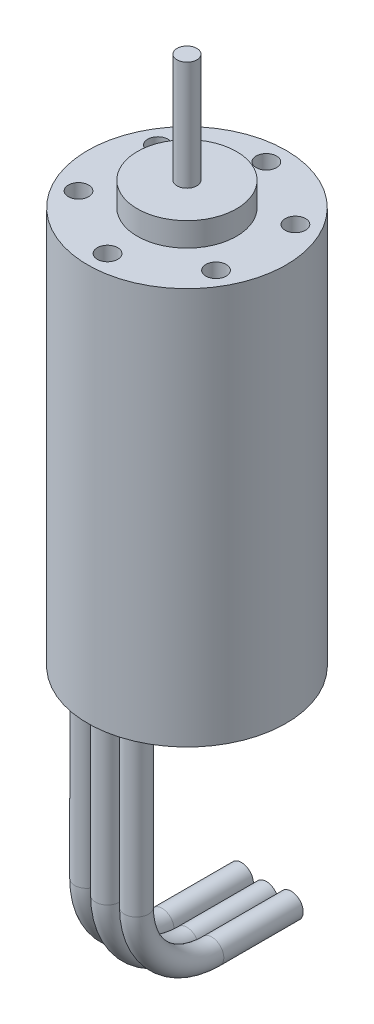
SolidWorks part; units mm, degrees
ref_plane "Front Plane" through (0, 0, 0) normal (0, 0, 1) x (1, 0, 0)
ref_plane "Top Plane" through (0, 0, 0) normal (0, 1, 0) x (1, 0, 0)
ref_plane "Right Plane" through (0, 0, 0) normal (1, 0, 0) x (0, 0, -1)
sketch "Sketch1" plane through (0, 0, 0) normal (0, 0, 1) x (1, 0, 0)
  line L0 (0, 0) -> (0, 55.8) construction
  line L1 (0, 55.8) -> (1, 55.8)
  line L2 (1, 55.8) -> (1, 44.8)
  line L3 (1, 44.8) -> (5, 44.8)
  line L4 (10, 42.4) -> (10, 2.4)
  line L5 (0, 0) -> (5, 0)
  line L6 (0, 0) -> (0, 55.8)
  line L7 (5, 0) -> (5, 2.4)
  line L8 (5, 2.4) -> (10, 2.4)
  line L9 (5, 44.8) -> (5, 42.4)
  line L10 (5, 42.4) -> (10, 42.4)
  dimension "D1" = 2.4
  dimension "D2" = 20
  dimension "D3" = 2
  dimension "D4" = 40
  dimension "D5" = 2.4
  dimension "D6" = 11
  dimension "D7" = 5
  dimension "D8" = 5
revolve "Revolve1" add sketch "Sketch1" angle 360 about L0
hole_wizard "M2.5x0.45 Tapped Hole1" positions "Sketch3" profile "Sketch2" tap size "M2.5x0.45" standard "ANSI Metric"
sketch "Sketch3" plane through (0, 42.4, 0) normal (0, 1, 0) x (1, 0, 0)
  line L1 (0, 0) -> (0, 8) construction
  point P0 (0, 8)
  dimension "D1" = 8
sketch "Sketch2" plane through (0, 42.4, -8) normal (1, 0, 0) x (0, 0, 1)
  line L0 (0, 0) -> (0, 4.6159)
  line L1 (0, 4.6159) -> (1.025, 4)
  line L2 (1.025, 4) -> (1.025, 0)
  line L5 (1.025, 0) -> (0, 0)
  line L10 (0, 4.6159) -> (-1.025, 4) construction
  line L11 (0, -6.35) -> (0, 107.95) construction
  dimension "Tap Drill Dia." = 2.05
  dimension "Tap Drill Depth" = 4
  dimension "Drill Angle" = 118
cosmetic thread "Hole Thread1" parameters "D1"=4, "D2"=2.5
pattern_circular "CirPattern1" count 6 over 360 about axis through (0, 0, 0) along (0, 1, 0) of "M2.5x0.45 Tapped Hole1"
sketch "Sketch4" plane through (0, 2.4, 0) normal (0, -1, 0) x (-1, 0, 0)
  line L0 (2.5078, -7.5968) -> (0, -8) construction
  line L1 (0, -8) -> (-2.5078, -7.5968) construction
  line L2 (-2.5078, -7.5968) -> (0, 0) construction
  line L3 (0, 0) -> (0, -8) construction
  line L4 (2.5078, -7.5968) -> (0, 0) construction
  circle A0 centre (-2.5078, -7.5968) radius 1.2065
  circle A1 centre (0, -8) radius 1.2065
  circle A2 centre (2.5078, -7.5968) radius 1.2065
  point P0 (-2.5078, -7.5968)
  point P1 (0, -8)
  point P2 (2.5078, -7.5968)
  dimension "D1" = 2.413
  dimension "D2" = 2.54
  dimension "D3" = 2.54
  dimension "D4" = 8
sketch "Sketch5" plane through (0, 0, 0) normal (1, 0, 0) x (0, 0, -1)
  line L0 (-8, 2.4) -> (-8, -13.6)
  line L1 (0, -21.6) -> (8, -21.6)
  arc A0 (-8, -13.6) -> (0, -21.6) centre (0, -13.6) ccw
  dimension "D2" = 8
  dimension "D1" = 24
  dimension "D3" = 8
sweep "Sweep1" add profiles "Sketch4" path "Sketch5"
